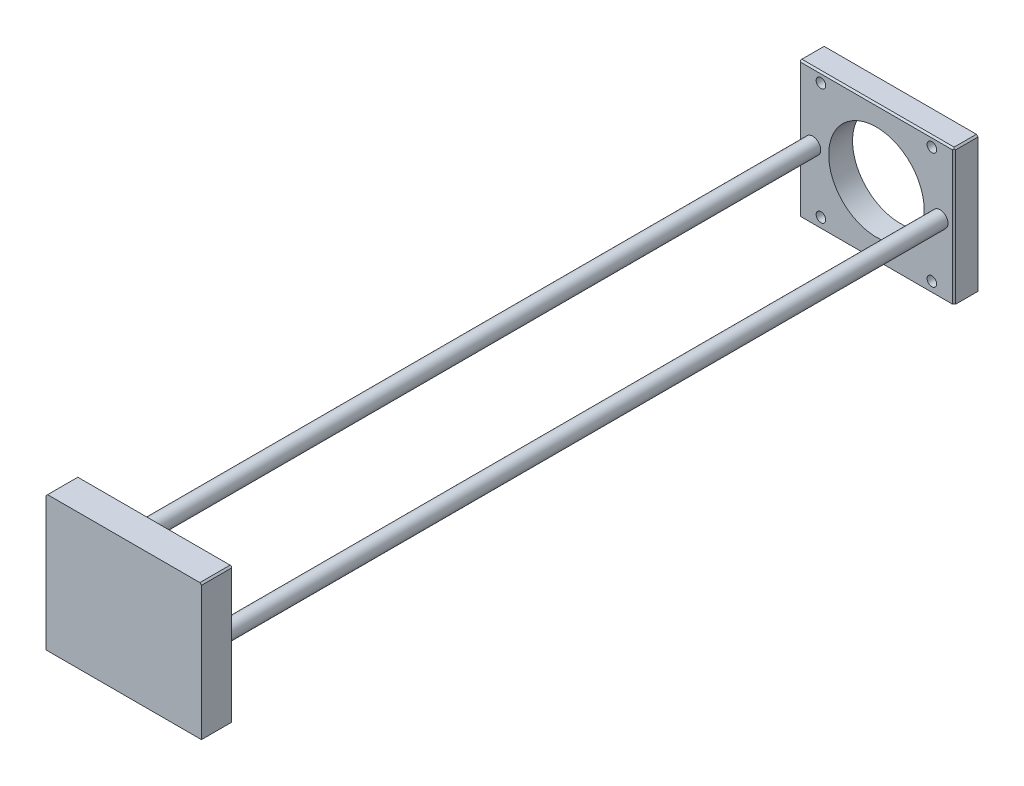
SolidWorks part; units mm, degrees
ref_plane "Alzado" through (0, 0, 0) normal (0, 0, 1) x (1, 0, 0)
ref_plane "Planta" through (0, 0, 0) normal (0, 1, 0) x (1, 0, 0)
ref_plane "Vista lateral" through (0, 0, 0) normal (1, 0, 0) x (0, 0, -1)
sketch "Croquis1" plane through (0, 0, 0) normal (0, 0, 1) x (1, 0, 0)
  line L0 (-34.85, 42.5) -> (-34.85, 36.5) construction
  line L1 (48.85, -42.5) -> (-48.85, -42.5)
  line L2 (48.85, -42.5) -> (48.85, 42.5)
  line L3 (48.85, 42.5) -> (-48.85, 42.5)
  line L4 (-48.85, -42.5) -> (-48.85, 42.5)
  line L5 (48.85, -42.5) -> (-48.85, 42.5) construction
  line L6 (48.85, 42.5) -> (-48.85, -42.5) construction
  line L7 (-34.85, 36.5) -> (-48.85, 36.5) construction
  line L8 (0, 42.5) -> (0, -42.5) construction
  line L9 (-48.85, 0) -> (48.85, 0) construction
  circle A0 centre (-34.85, 36.5) radius 3
  circle A1 centre (0, 0) radius 30
  circle A2 centre (34.85, 36.5) radius 3
  circle A3 centre (34.85, -36.5) radius 3
  circle A4 centre (-34.85, -36.5) radius 3
  point P0 (0, 0)
  dimension "D5" = 6
  dimension "D6" = 60
  dimension "D1" = 97.7
  dimension "D2" = 85
  dimension "D3" = 6
  dimension "D4" = 14
extrude "Saliente-Extruir1" add sketch "Croquis1" along normal blind 15
sketch "Croquis2" plane through (0, 0, 15) normal (0, 0, 1) x (1, 0, 0)
  line L0 (-34.85, 36.5) -> (-34.85, -36.5) construction
  line L1 (34.85, 36.5) -> (34.85, -36.5) construction
  line L3 (0, 42.5) -> (0, -42.5) construction
  line L4 (48.85, 42.5) -> (-48.85, 42.5) construction
  line L5 (-48.85, -42.5) -> (48.85, -42.5) construction
  circle A1 centre (-40, 0) radius 5
  circle A2 centre (40, 0) radius 5
  point P15 (0, 0)
  dimension "D1" = 10
  dimension "D2" = 40
extrude "Saliente-Extruir2" add sketch "Croquis2" along normal blind 453
ref_plane "Plano1" through (0, 0, 465) normal (0, 0, 1) x (1, 0, 0)
sketch "Croquis3" plane through (0, 0, 465) normal (0, 0, 1) x (1, 0, 0)
  line L1 (-48.85, 42.5) -> (48.85, 42.5)
  line L2 (-48.85, 42.5) -> (-48.85, -42.5)
  line L3 (-48.85, -42.5) -> (48.85, -42.5)
  line L4 (48.85, 42.5) -> (48.85, -42.5)
extrude "Saliente-Extruir3" add sketch "Croquis3" along normal blind 20 from surface at 3 starting at face at (-35, 0, 468)
chamfer "Chaflán1" distance 1 angle 45 6 edges at (-48.85, 0, 15) (0, 42.5, 15) (48.85, 0, 15) (-48.85, 0, 468) (0, 42.5, 468) (48.85, 0, 468)
chamfer "Chaflán2" distance 1 angle 45 4 edges at (-48.85, 42.5, 7) (48.85, 42.5, 7) (-48.85, 42.5, 478.5) (48.85, 42.5, 478.5)
